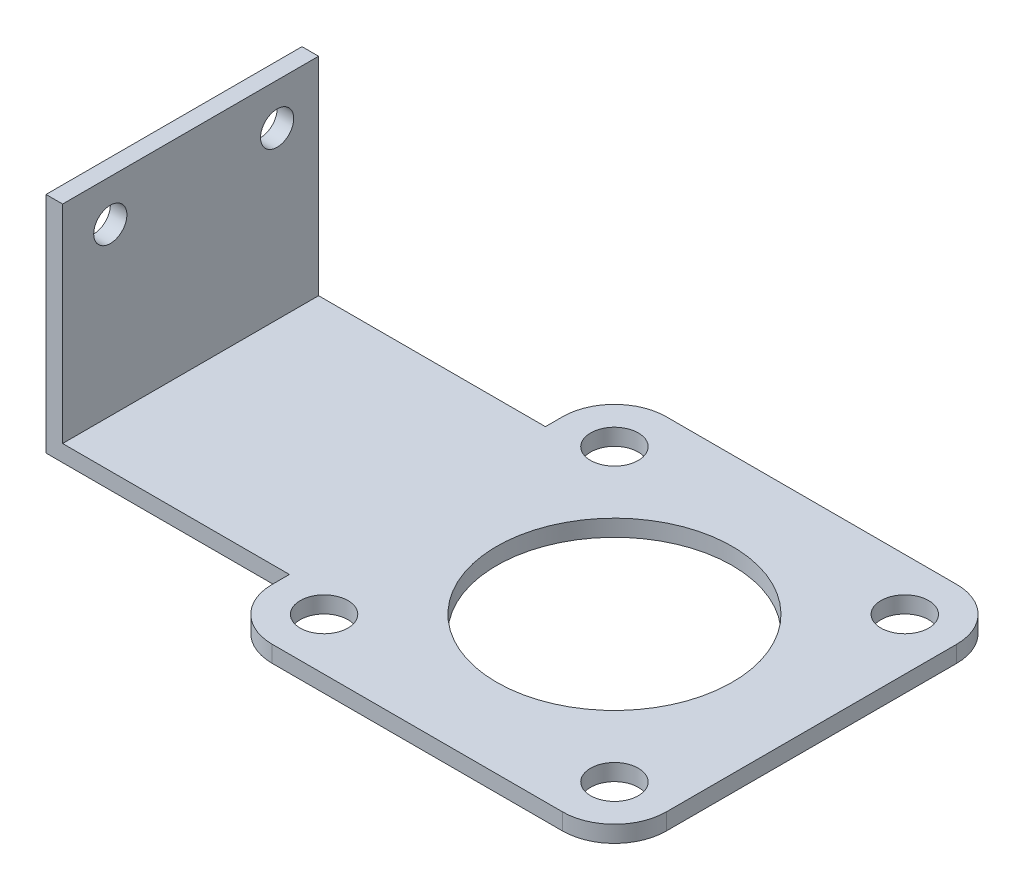
SolidWorks part; units mm, degrees
ref_plane "Front" through (0, 0, 0) normal (0, 0, 1) x (1, 0, 0)
ref_plane "Top" through (0, 0, 0) normal (0, 1, 0) x (1, 0, 0)
ref_plane "Right" through (0, 0, 0) normal (1, 0, 0) x (0, 0, -1)
sketch "Sketch1" plane through (0, 0, 0) normal (0, 1, 0) x (1, 0, 0)
  line L0 (12.5, 0) -> (82.5, 0)
  line L1 (0, 12.5) -> (0, 82.5)
  line L2 (12.5, 95) -> (82.5, 95)
  line L3 (95, 82.5) -> (95, 12.5)
  arc A0 (82.5, 95) -> (95, 82.5) centre (82.5, 82.5) cw
  arc A1 (95, 12.5) -> (82.5, 0) centre (82.5, 12.5) cw
  arc A2 (12.5, 0) -> (0, 12.5) centre (12.5, 12.5) cw
  arc A3 (12.5, 95) -> (0, 82.5) centre (12.5, 82.5) ccw
  point P9 (95, 0)
  point P12 (0, 0)
  point P15 (0, 95)
  dimension "D3" = 12.5
  dimension "D1" = 95
  dimension "D2" = 95
extrude "Boss-Extrude1" add sketch "Sketch1" along normal blind 4
sketch "Sketch2" plane through (0, 4, 0) normal (0, 1, 0) x (1, 0, 0)
  line L0 (47.5, 95) -> (47.5, 0) construction
  line L1 (82.5, 95) -> (12.5, 95) construction
  line L2 (12.5, 0) -> (82.5, 0) construction
  line L3 (12.5, 95) -> (12.5, 82.5) construction
  line L4 (0, 82.5) -> (12.5, 82.5) construction
  line L5 (95, 82.5) -> (82.5, 82.5) construction
  line L6 (82.5, 95) -> (82.5, 82.5) construction
  line L7 (0, 12.5) -> (12.5, 12.5) construction
  line L8 (95, 12.5) -> (82.5, 12.5) construction
  circle A1 centre (12.5, 82.5) radius 5.75
  circle A2 centre (82.5, 82.5) radius 5.75
  circle A3 centre (12.5, 12.5) radius 5.75
  circle A4 centre (82.5, 12.5) radius 5.75
  dimension "D3" = 11.5
  dimension "D6" = 11.5
  dimension "D7" = 11.5
  dimension "D9" = 11.5
  dimension "D2" = 12.5
  dimension "D8" = 12.5
extrude "Cut-Extrude1" cut sketch "Sketch2" against normal blind 10 and the other way blind 10
sketch "Sketch8" plane through (0, 0, 0) normal (-1, 0, 0) x (0, 0, 1)
  line L0 (-17.6413, 4) -> (-16.6413, 4)
  line L1 (-17.6413, 4) -> (-77.3587, 4)
  line L21 (-77.3587, 4) -> (-78.3587, 4)
  line L25 (-78.3587, 4) -> (-78.3587, 0)
  line L26 (-82.5, 0) -> (-12.5, 0) construction
  line L27 (-78.3587, 0) -> (-16.6413, 0)
  line L28 (-16.6413, 0) -> (-16.6413, 4)
  point P5 (-47.5, 4)
extrude "Boss-Extrude5" add sketch "Sketch8" along normal blind 58.68
sketch "Sketch12" plane through (0, 4, 0) normal (0, 1, 0) x (1, 0, 0)
  line L2 (-58.68, 78.3587) -> (-54.68, 78.3587)
  line L4 (-58.68, 78.3587) -> (0, 78.3587) construction
  line L12 (-54.68, 78.3587) -> (-54.68, 16.6413)
  line L13 (-58.68, 16.6413) -> (0, 16.6413) construction
  line L14 (-54.68, 16.6413) -> (-58.68, 16.6413)
  line L15 (-58.68, 16.6413) -> (-58.68, 78.3587)
  dimension "D1" = 4
extrude "Boss-Extrude8" add sketch "Sketch12" along normal blind 50
sketch "Sketch13" plane through (-58.68, 0, 0) normal (-1, 0, 0) x (0, 0, 1)
  line L0 (-68.3587, 44) -> (-78.3587, 44) construction
  line L1 (-78.3587, 54) -> (-78.3587, 0) construction
  line L2 (-68.3587, 44) -> (-68.3587, 54) construction
  line L3 (-78.3587, 54) -> (-16.6413, 54) construction
  line L4 (-28.1413, 54) -> (-28.1413, 44) construction
  line L5 (-28.1413, 44) -> (-16.6413, 44) construction
  line L6 (-16.6413, 0) -> (-16.6413, 54) construction
  circle A0 centre (-68.3587, 44) radius 4
  circle A1 centre (-28.1413, 44) radius 4
  dimension "D2" = 8
  dimension "D5" = 8
  dimension "D1" = 10
  dimension "D3" = 10
  dimension "D4" = 10
  dimension "D6" = 11.5
extrude "Cut-Extrude5" cut sketch "Sketch13" against normal blind 20
sketch "Sketch14" plane through (0, 4, 0) normal (0, 1, 0) x (1, 0, 0)
  line L0 (47.5, 95) -> (47.5, 0) construction
  line L1 (82.5, 95) -> (12.5, 95) construction
  line L2 (12.5, 0) -> (82.5, 0) construction
  circle A0 centre (47.5, 47.5) radius 28.395
  dimension "D1" = 56.79
extrude "Cut-Extrude6" cut sketch "Sketch14" against normal blind 10
